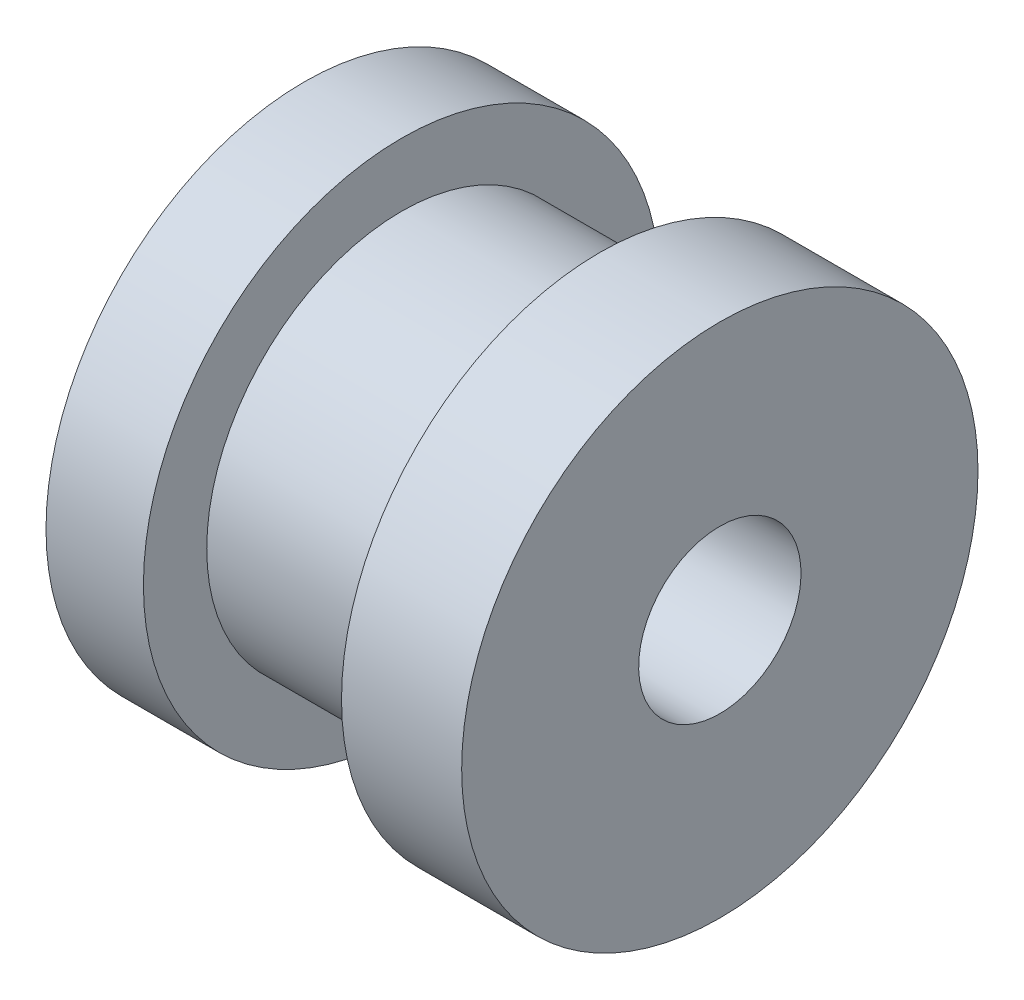
SolidWorks part; units mm, degrees
material "2014-O"
ref_plane "Спереди" through (0, 0, 0) normal (0, 0, 1) x (1, 0, 0)
ref_plane "Сверху" through (0, 0, 0) normal (0, 1, 0) x (1, 0, 0)
ref_plane "Справа" through (0, 0, 0) normal (1, 0, 0) x (0, 0, -1)
sketch "Эскиз2" plane through (0, 0, 0) normal (0, 0, 1) x (1, 0, 0)
  line L0 (0, 0) -> (-12.8, 0) construction
  line L1 (-12.8, 2.5) -> (-12.8, 7.95)
  line L2 (-12.8, 7.95) -> (-9.8, 7.95)
  line L3 (-9.8, 7.95) -> (-9.8, 6)
  line L4 (-9.8, 6) -> (-3.7, 6)
  line L5 (-3.7, 6) -> (-3.7, 7.95)
  line L6 (-3.7, 7.95) -> (0, 7.95)
  line L7 (0, 7.95) -> (0, 2.5)
  line L8 (0, 2.5) -> (-12.8, 2.5)
  dimension "D1" = 15.9
  dimension "D2" = 12
  dimension "D3" = 3.7
  dimension "D4" = 6.1
  dimension "D5" = 12.8
  dimension "D6" = 3
  dimension "D7" = 5
revolve "Повернуть1" add sketch "Эскиз2" angle 360 about L0
hole_wizard "Отверстие обработанное метчиком G1/81" positions "Трехмерный эскиз1" profile "Эскиз4" tap size "G1/8" standard "AS"
sketch3d "Трехмерный эскиз1"
  line L0 (-12.8, 0, 0) -> (0, 0, 0) construction
  point P7 (-12.8, 0, 0)
cosmetic thread "Отверстие резьбы1" parameters "D1"=8, "D2"=9.728
sketch "Эскиз4" plane through (-12.8, 0, 0) normal (0, 1, 0) x (0, 0, 1)
  line L0 (0, 0) -> (0, 9)
  line L1 (0, 9) -> (4.4, 9)
  line L2 (4.4, 9) -> (4.4, 1.25)
  line L3 (4.4, 1.25) -> (5.65, 0)
  line L5 (5.65, 0) -> (0, 0)
  line L6 (-4.4, 1.25) -> (-5.65, 0) construction
  line L10 (0, 9) -> (-4.4, 9) construction
  line L11 (0, -6.35) -> (0, 107.95) construction
  dimension "Диаметр сверла" = 8.8
  dimension "Глубина сверла" = 9
  dimension "Диаметр передней зенковки" = 11.3
  dimension "Угол передней зенковки" = 90
  dimension "Угол заточки сверла" = 180
